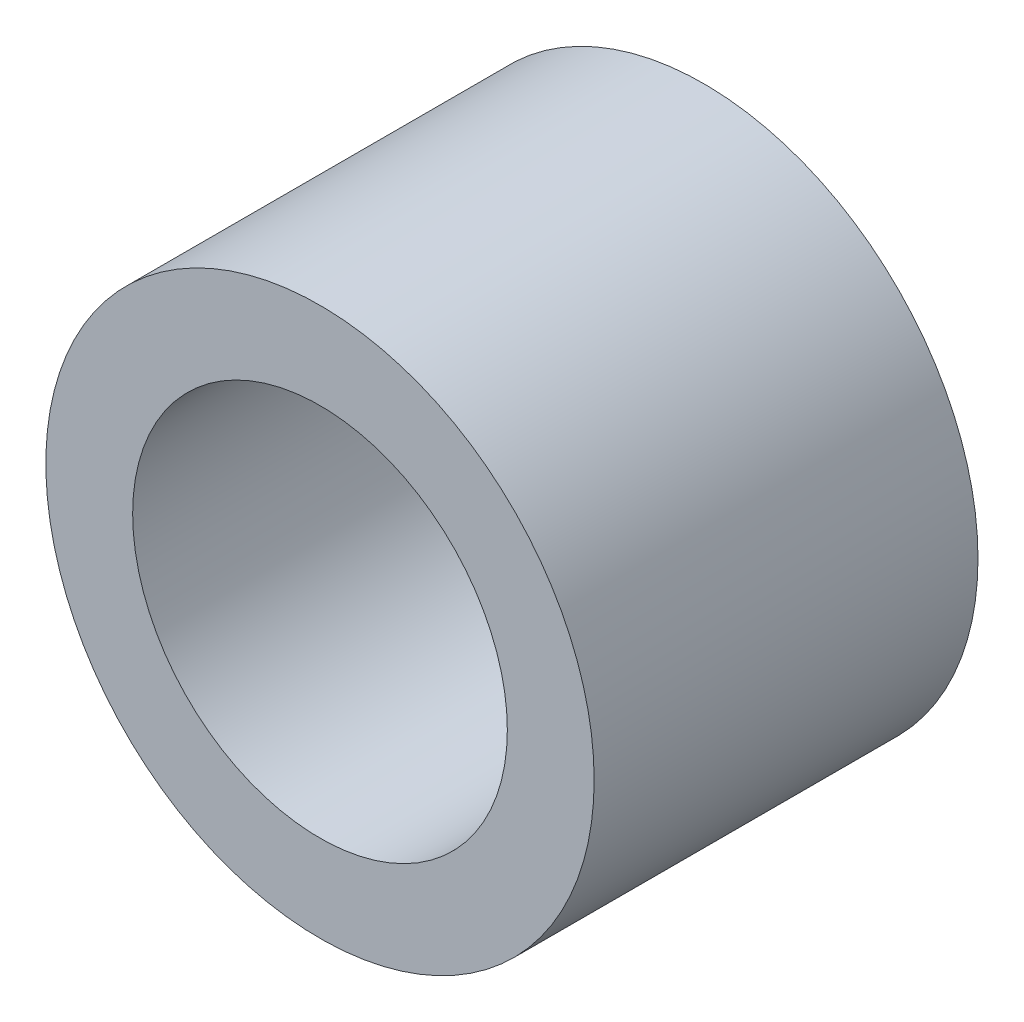
SolidWorks part; units mm, degrees
ref_plane "Front Plane" through (0, 0, 0) normal (0, 0, 1) x (1, 0, 0)
ref_plane "Top Plane" through (0, 0, 0) normal (0, 1, 0) x (1, 0, 0)
ref_plane "Right Plane" through (0, 0, 0) normal (1, 0, 0) x (0, 0, -1)
sketch "S01 - Smooth cylindrical section" plane through (0, 0, 0) normal (0, 0, 1) x (1, 0, 0)
  circle A0 centre (0, 0) radius 3
  circle A1 centre (0, 0) radius 2.05
  dimension "D1" = 4.1
  dimension "D2" = 6
extrude "01 - Smooth cylindrical section" add sketch "S01 - Smooth cylindrical section" along normal blind 4.2
